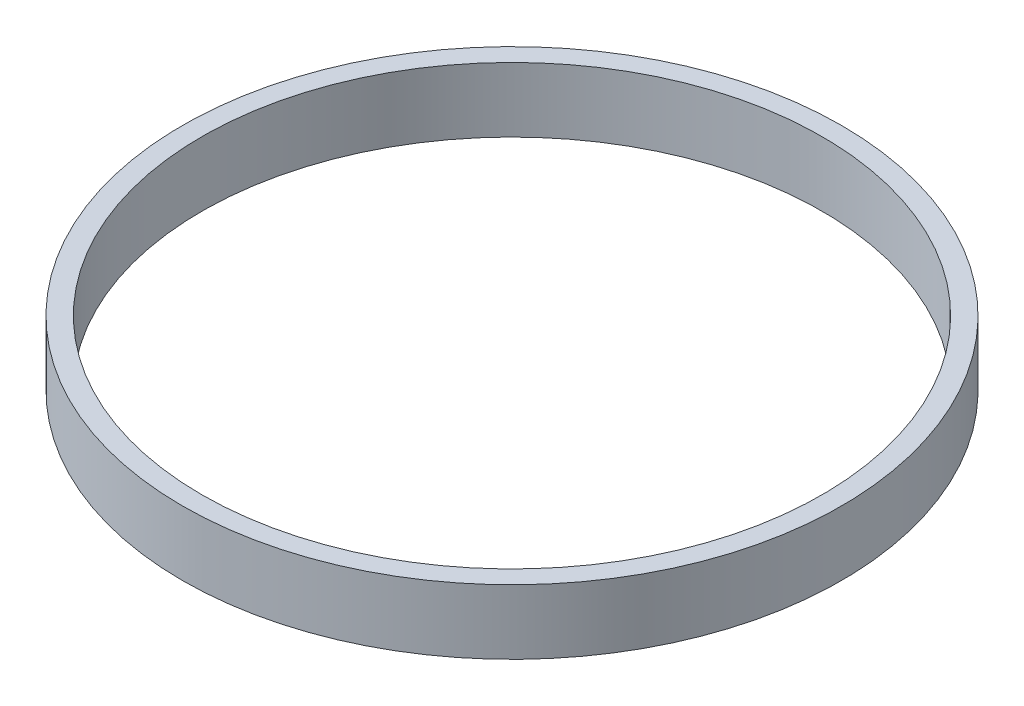
SolidWorks part; units mm, degrees
material "BUTYL"
ref_plane "Front Plane" through (0, 0, 0) normal (0, 0, 1) x (1, 0, 0)
ref_plane "Top Plane" through (0, 0, 0) normal (0, 1, 0) x (1, 0, 0)
ref_plane "Right Plane" through (0, 0, 0) normal (1, 0, 0) x (0, 0, -1)
sketch "Sketch1" plane through (0, 0, 0) normal (0, 1, 0) x (1, 0, 0)
  circle A0 centre (0, 0) radius 24
  circle A1 centre (0, 0) radius 25.5
  dimension "D1" = 48
  dimension "D2" = 51
extrude "Boss-Extrude1" add sketch "Sketch1" along normal blind 5
